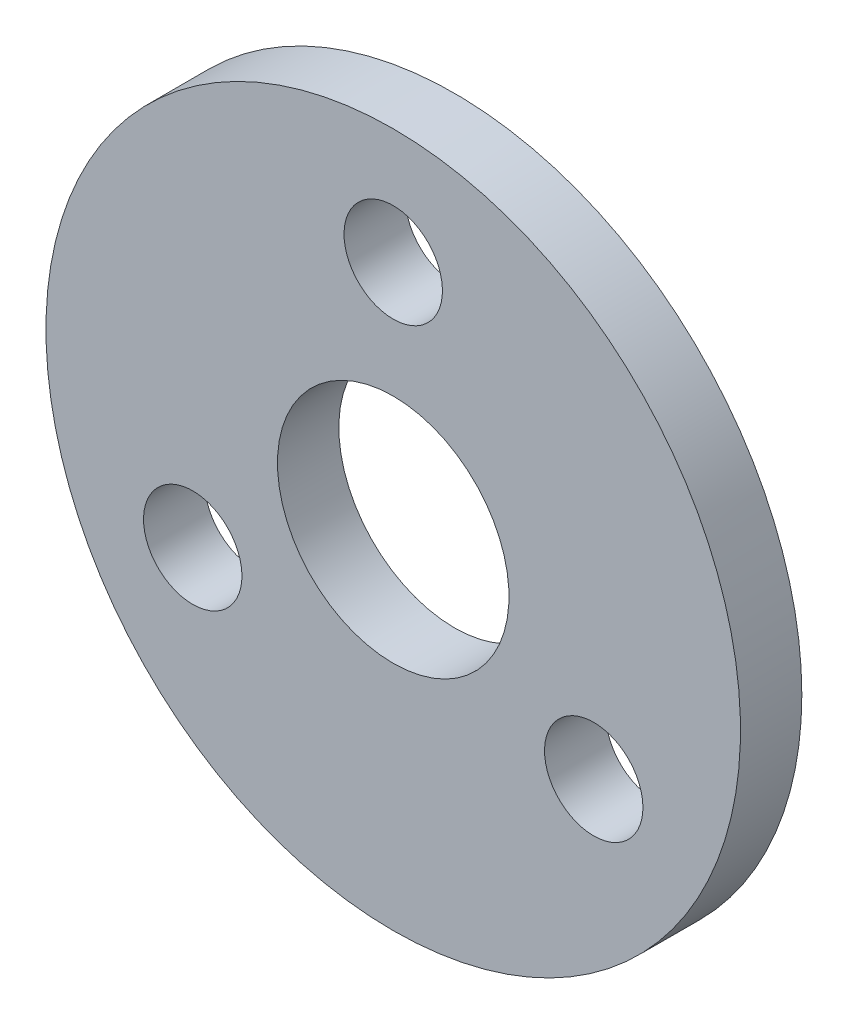
SolidWorks part; units mm, degrees
material "PET"
ref_plane "Front Plane" through (0, 0, 0) normal (0, 0, 1) x (1, 0, 0)
ref_plane "Top Plane" through (0, 0, 0) normal (0, 1, 0) x (1, 0, 0)
ref_plane "Right Plane" through (0, 0, 0) normal (1, 0, 0) x (0, 0, -1)
sketch "Sketch1" plane through (0, 0, 0) normal (0, 0, 1) x (1, 0, 0)
  circle A0 centre (-6.9282, -4) radius 1.7 construction
  circle A1 centre (0, 0) radius 12
  circle A2 centre (0, 0) radius 12
  circle A3 centre (6.9282, -4) radius 1.7 construction
  circle A5 centre (0, 8) radius 1.7 construction
  circle A6 centre (-6.9282, -4) radius 1.7
  circle A7 centre (6.9282, -4) radius 1.7
  circle A9 centre (0, 8) radius 1.7
  circle A11 centre (0, 0) radius 4 construction
  circle A12 centre (0, 0) radius 4
  dimension "D1" = 0
extrude "Boss-Extrude1" add sketch "Sketch1" along normal up to surface (2.12 mm away) from offset 9.525
